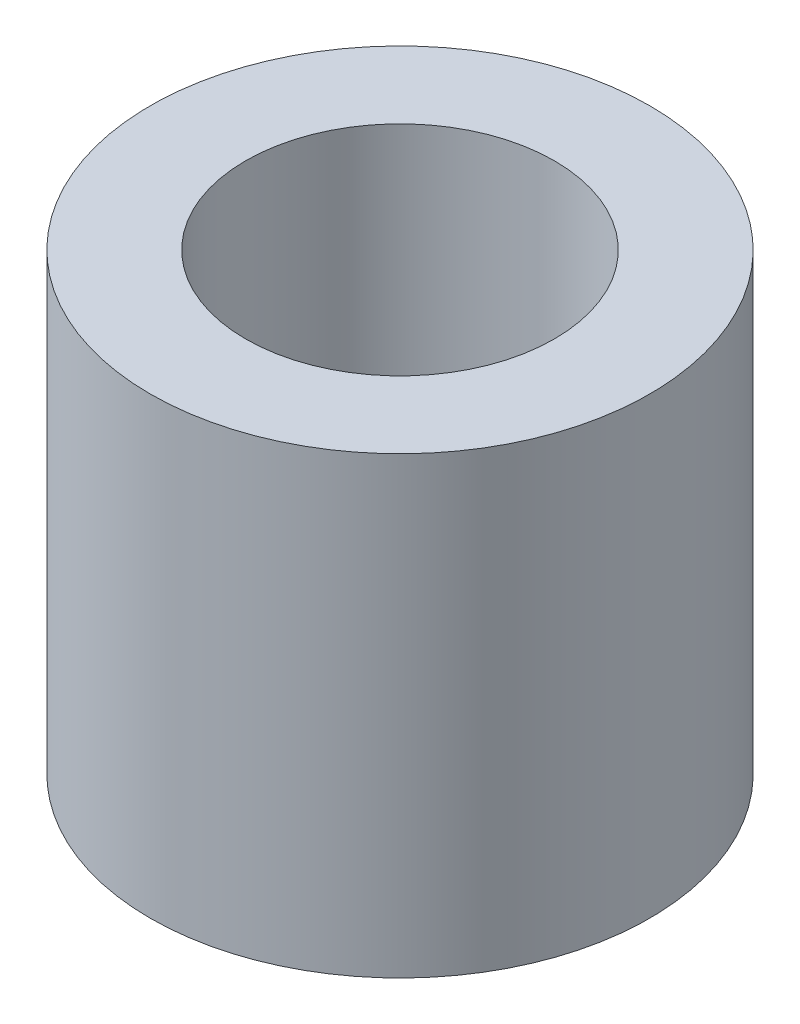
SolidWorks part; units mm, degrees
ref_plane "Front Plane" through (0, 0, 0) normal (0, 0, 1) x (1, 0, 0)
ref_plane "Top Plane" through (0, 0, 0) normal (0, 1, 0) x (1, 0, 0)
ref_plane "Right Plane" through (0, 0, 0) normal (1, 0, 0) x (0, 0, -1)
sketch "Sketch1" plane through (0, 0, 0) normal (0, 1, 0) x (1, 0, 0)
  circle A0 centre (0, 0) radius 1.7
  circle A1 centre (0, 0) radius 2.75
  point P3 (0, 0)
  dimension "D1" = 3.4
  dimension "D2" = 5.5
extrude "Boss-Extrude1" add sketch "Sketch1" along normal blind 5
